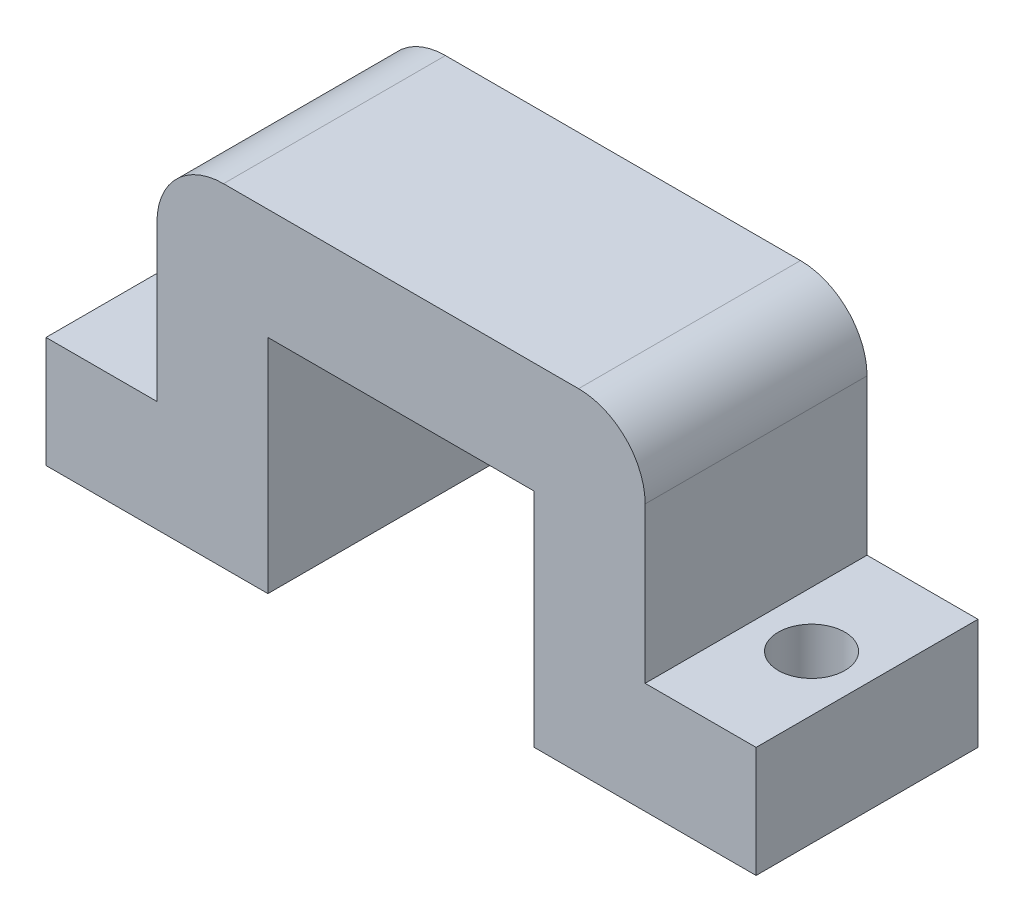
SolidWorks part; units mm, degrees
ref_plane "Plan de face" through (0, 0, 0) normal (0, 0, 1) x (1, 0, 0)
ref_plane "Plan de dessus" through (0, 0, 0) normal (0, 1, 0) x (1, 0, 0)
ref_plane "Plan de droite" through (0, 0, 0) normal (1, 0, 0) x (0, 0, -1)
sketch "Esquisse1" plane through (0, 0, 0) normal (0, 0, 1) x (1, 0, 0)
  line L0 (0, 1.3736) -> (0, 11.3736)
  line L1 (0, 11.3736) -> (12, 11.3736)
  line L2 (12, 11.3736) -> (12, 1.3736)
  line L3 (0, 1.3736) -> (-10, 1.3736)
  line L4 (12, 1.3736) -> (22, 1.3736)
  line L5 (17, 6.3736) -> (22, 6.3736)
  line L6 (17, 13.3736) -> (17, 6.3736)
  line L7 (-2, 16.3736) -> (14, 16.3736)
  line L8 (-5, 6.3736) -> (-5, 13.3736)
  line L9 (-5, 6.3736) -> (-10, 6.3736)
  line L10 (-10, 6.3736) -> (-10, 1.3736)
  line L11 (22, 6.3736) -> (22, 1.3736)
  line L12 (17, 16.3736) -> (17, 6.3736) construction
  line L13 (-5, 16.3736) -> (17, 16.3736) construction
  line L14 (-5, 6.3736) -> (-5, 16.3736) construction
  arc A0 (17, 13.3736) -> (14, 16.3736) centre (14, 13.3736) ccw
  arc A1 (-2, 16.3736) -> (-5, 13.3736) centre (-2, 13.3736) ccw
  dimension "D6" = 3
  dimension "D1" = 10
  dimension "D2" = 12
  dimension "D3" = 10
  dimension "D4" = 10
  dimension "D5" = 5
extrude "Boss.-Extru.1" add sketch "Esquisse1" along normal blind 10
sketch "Esquisse2" plane through (0, 6.3736, 0) normal (0, 1, 0) x (1, 0, 0)
  line L0 (-13.7691, -10) -> (29.6911, -10) construction
  line L1 (6, 7.2587) -> (6, -27.2484) construction
  line L4 (-5, 0) -> (-10, 0)
  line L5 (-10, 0) -> (-10, -10)
  line L6 (-10, -10) -> (-5, -10)
  line L7 (-5, -10) -> (-5, 0)
  line L8 (-5, 0) -> (-10, 0)
  line L9 (-10, 0) -> (-10, -10)
  line L10 (-10, -10) -> (-5, -10)
  line L11 (-5, -10) -> (-5, 0)
  circle A0 centre (-7.5, -5) radius 1.5
  circle A1 centre (-7.5, -15) radius 1.5
  circle A2 centre (19.5, -15) radius 1.5
  circle A3 centre (19.5, -5) radius 1.5
  dimension "D2" = 3
  dimension "D3" = 5
  dimension "D1" = 0
extrude "Enlèv. mat.-Extru.1" cut sketch "Esquisse2" against normal blind 20 contours A1 | A0 | A3 | A2
